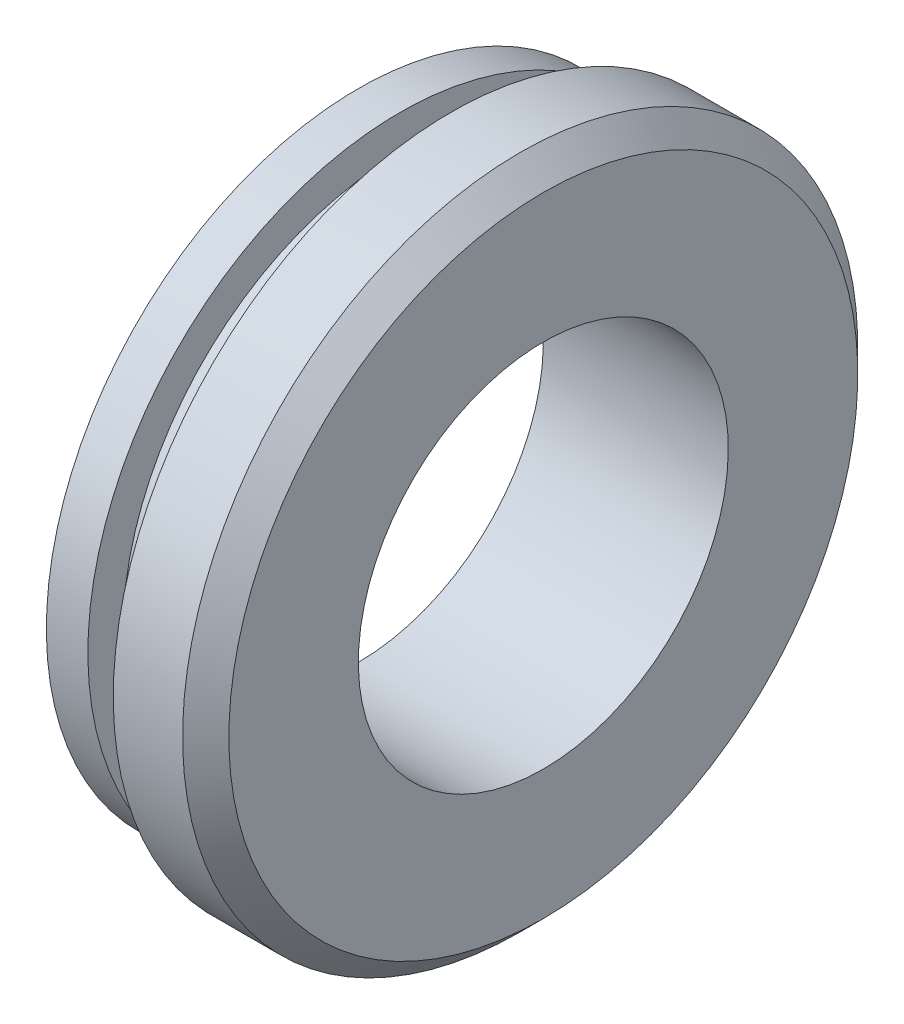
SolidWorks part; units mm, degrees
material "PBT Общее назначение"
ref_plane "Спереди" through (0, 0, 0) normal (0, 0, 1) x (1, 0, 0)
ref_plane "Сверху" through (0, 0, 0) normal (0, 1, 0) x (1, 0, 0)
ref_plane "Справа" through (0, 0, 0) normal (1, 0, 0) x (0, 0, -1)
sketch "Эскиз2" plane through (0, 0, 0) normal (0, 0, 1) x (1, 0, 0)
  line L0 (0, 6.8983) -> (0, 8)
  line L1 (0, 8) -> (8.5, 8)
  line L2 (8.5, 8) -> (8.5, 7.3)
  line L3 (8.5, 7.3) -> (14.5, 7.3)
  line L5 (14.5, 7.3) -> (16.5, 7.3)
  line L6 (16.5, 7.3) -> (16.5, 4)
  line L7 (16.5, 4) -> (12.5, 4)
  line L8 (12.5, 4) -> (12.5, 4.991)
  line L9 (12.5, 4.991) -> (0.7, 4.991)
  line L12 (0, 0) -> (0, 6.8983) construction
  line L13 (0, 6.8983) -> (0.7, 6.8983)
  line L16 (0.7, 6.8983) -> (0.7, 4.991)
  line L17 (0, 0) -> (18.5797, 0) construction
  line L18 (12.5, 4.991) -> (12.5, 6.7463)
  line L19 (12.5, 6.7463) -> (13.3974, 6.7463)
  line L20 (13.3974, 6.7463) -> (13.3974, 5.991)
  line L21 (13.3974, 5.991) -> (14.5, 5.991)
  line L22 (14.5, 5.991) -> (14.5, 7.3)
  line L23 (14.5, 5.991) -> (14.5, 7.3)
  point P19 (14.5, 7.2654)
  dimension "D1" = 16.5
  dimension "D2" = 8
  dimension "D3" = 4.991
  dimension "D4" = 4
  dimension "D5" = 0.7
  dimension "D6" = 8.5
  dimension "D7" = 6
  dimension "D8" = 3.3
  dimension "D9" = 0.8974
  dimension "D10" = 4
  dimension "D11" = 0.7
  dimension "D12" = 1.9074
  dimension "D13" = 1.1026
  dimension "D14" = 0.7553
  dimension "D15" = 1.7553
revolve "Повернуть1" add sketch "Эскиз2" angle 360 about L17
cosmetic thread "Условное изображение резьбы1" parameters "D2"=8
chamfer "Фаска1" distance 0.5 angle 45 1 edges at (16.5, -7.3, 0)
